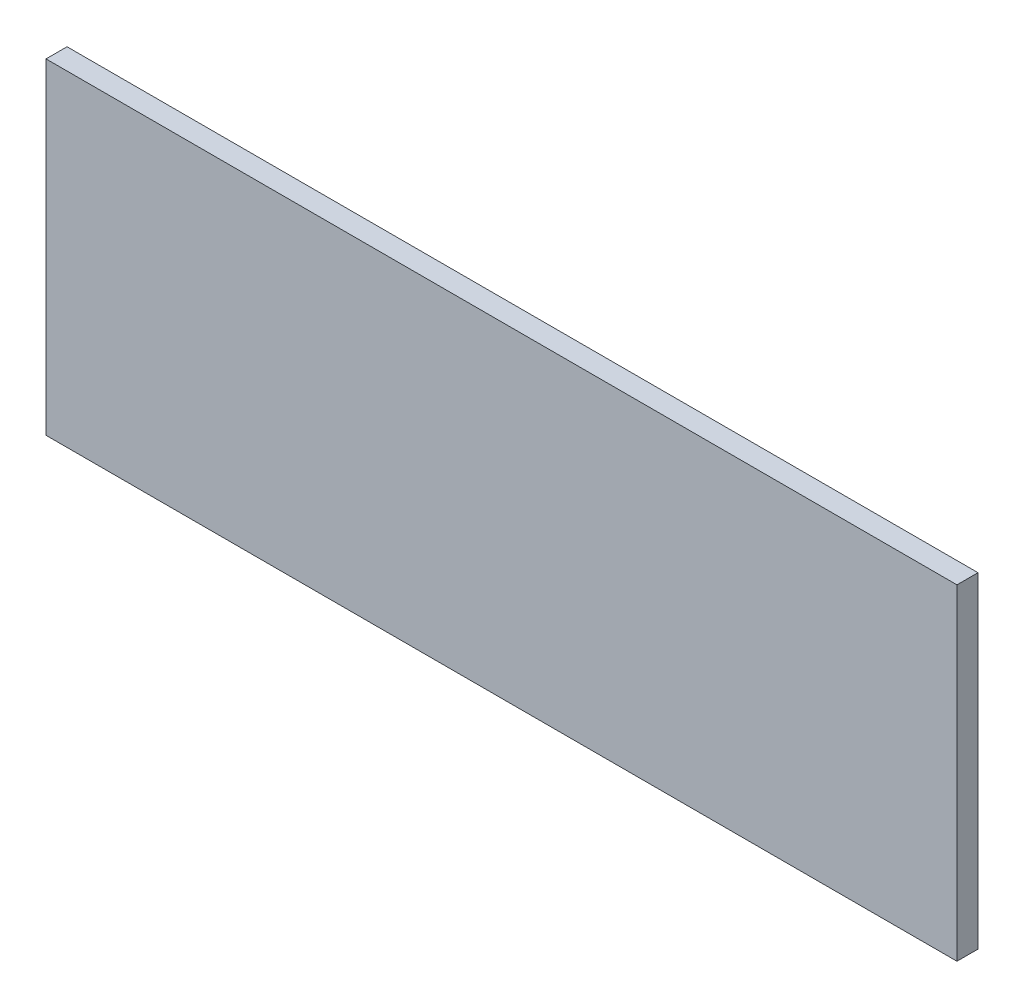
SolidWorks part; units mm, degrees
material "Q235A"
ref_plane "前视" through (0, 0, 0) normal (0, 0, 1) x (1, 0, 0)
ref_plane "上视" through (0, 0, 0) normal (0, 1, 0) x (1, 0, 0)
ref_plane "右视" through (0, 0, 0) normal (1, 0, 0) x (0, 0, -1)
sketch "草图1" plane through (0, 0, 0) normal (0, 0, 1) x (1, 0, 0)
  line L1 (346.5, -124) -> (-346.5, -124)
  line L2 (346.5, -124) -> (346.5, 124)
  line L3 (346.5, 124) -> (-346.5, 124)
  line L4 (-346.5, -124) -> (-346.5, 124)
  line L5 (346.5, -124) -> (-346.5, 124) construction
  line L6 (346.5, 124) -> (-346.5, -124) construction
  point P0 (0, 0)
  dimension "D1" = 248
  dimension "D2" = 693
extrude "凸台-拉伸1" add sketch "草图1" along normal blind 16
